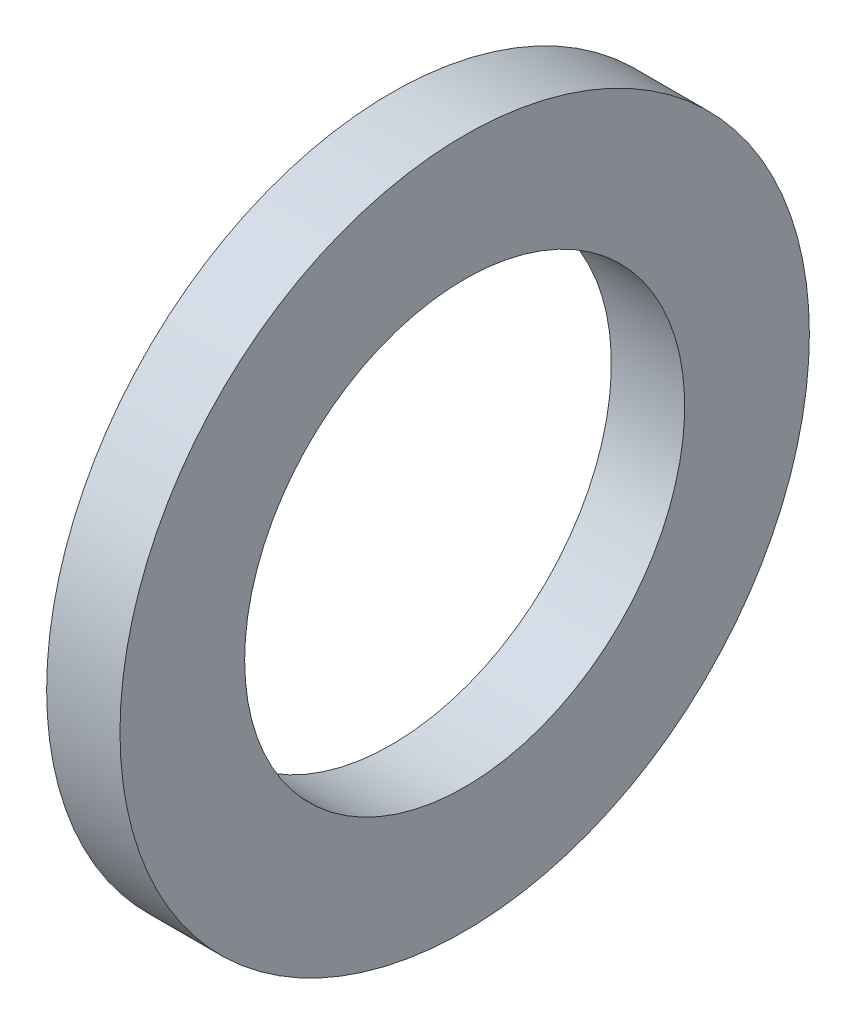
SolidWorks part; units mm, degrees
ref_plane "Płaszczyzna przednia" through (0, 0, 0) normal (0, 0, 1) x (1, 0, 0)
ref_plane "Płaszczyzna górna" through (0, 0, 0) normal (0, 1, 0) x (1, 0, 0)
ref_plane "Płaszczyzna prawa" through (0, 0, 0) normal (1, 0, 0) x (0, 0, -1)
sketch "Szkic1" plane through (0, 0, 0) normal (0, 0, 1) x (1, 0, 0)
  line L0 (-51.4495, -200.7423) -> (29.8196, -200.7423) construction
  line L1 (-11.5387, -177.2423) -> (-6.5387, -177.2423)
  line L2 (-11.5387, -177.2423) -> (-11.5387, -185.7423)
  line L3 (-11.5387, -185.7423) -> (-6.5387, -185.7423)
  line L4 (-6.5387, -177.2423) -> (-6.5387, -185.7423)
  dimension "D1" = 30
  dimension "D2" = 5
  dimension "D3" = 8.5
revolve "Obrót1" add sketch "Szkic1" angle 360 about L0
